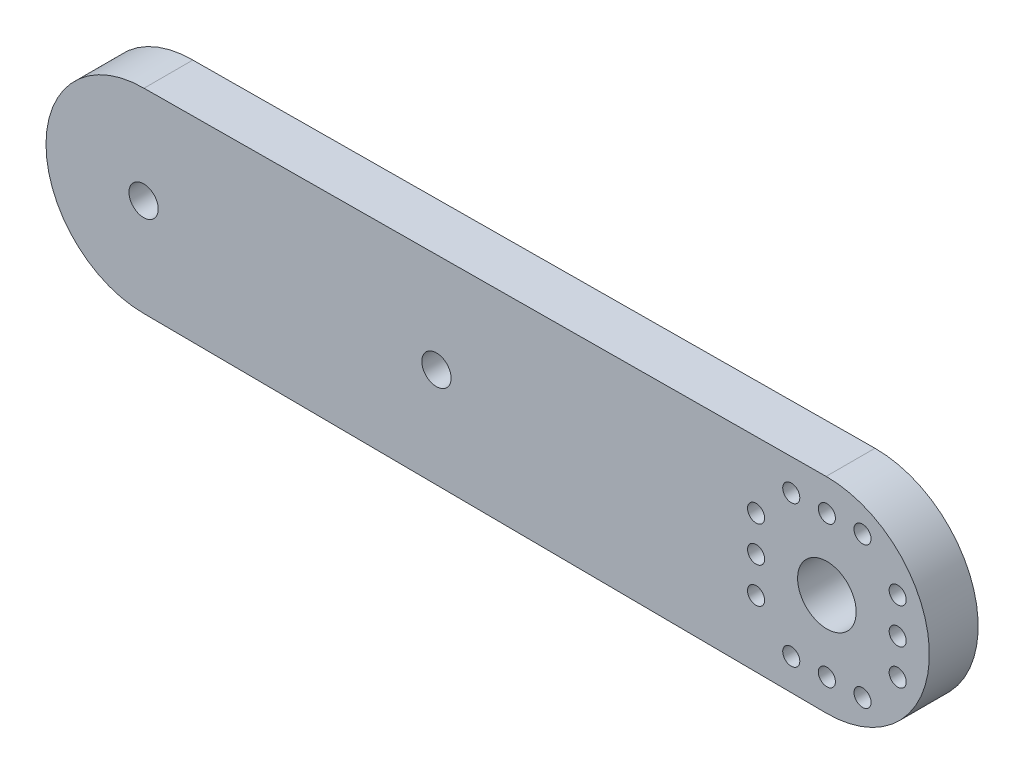
SolidWorks part; units mm, degrees
ref_plane "Plan de face" through (0, 0, 0) normal (0, 0, 1) x (1, 0, 0)
ref_plane "Plan de dessus" through (0, 0, 0) normal (0, 1, 0) x (1, 0, 0)
ref_plane "Plan de droite" through (0, 0, 0) normal (1, 0, 0) x (0, 0, -1)
sketch "Esquisse1" plane through (0, 0, 0) normal (0, 0, 1) x (1, 0, 0)
  line L0 (7.2545, 0) -> (7.2545, 12.5737) construction
  line L1 (0, 0) -> (7.2545, 0) construction
  line L2 (0, 0) -> (-70, 0) construction
  line L3 (-70, -10) -> (-0.075, -10.4997)
  line L4 (-69.9572, 9.9999) -> (-0.0751, 10.4997)
  arc A0 (-0.075, -10.4997) -> (-0.0751, 10.4997) centre (0, 0) ccw
  circle A1 centre (7.2545, 3.65) radius 0.875
  circle A2 centre (7.2545, 0) radius 0.875
  circle A3 centre (7.2545, -3.65) radius 0.875
  circle A4 centre (3.65, -7.2545) radius 0.875
  circle A5 centre (0, -7.2545) radius 0.875
  circle A6 centre (-3.65, -7.2545) radius 0.875
  circle A7 centre (-7.2545, -3.65) radius 0.875
  circle A8 centre (-7.2545, 0) radius 0.875
  circle A9 centre (-7.2545, 3.65) radius 0.875
  circle A10 centre (-3.65, 7.2545) radius 0.875
  circle A11 centre (0, 7.2545) radius 0.875
  circle A12 centre (3.65, 7.2545) radius 0.875
  arc A13 (-69.9572, 9.9999) -> (-70, -10) centre (-70, 0) ccw
  circle A14 centre (-70, 0) radius 1.5
  circle A15 centre (-40, 0) radius 1.5
  circle A16 centre (0, 0) radius 3
  point P31 (0, 0)
  dimension "D1" = 1.75
  dimension "D2" = 21
  dimension "D4" = 1.75
  dimension "D8" = 10
  dimension "D9" = 30
  dimension "D3" = 7.2545
  dimension "D5" = 3.65
  dimension "D6" = 4
  dimension "D7" = 70
extrude "Boss.-Extru.1" add sketch "Esquisse1" along normal blind 5
